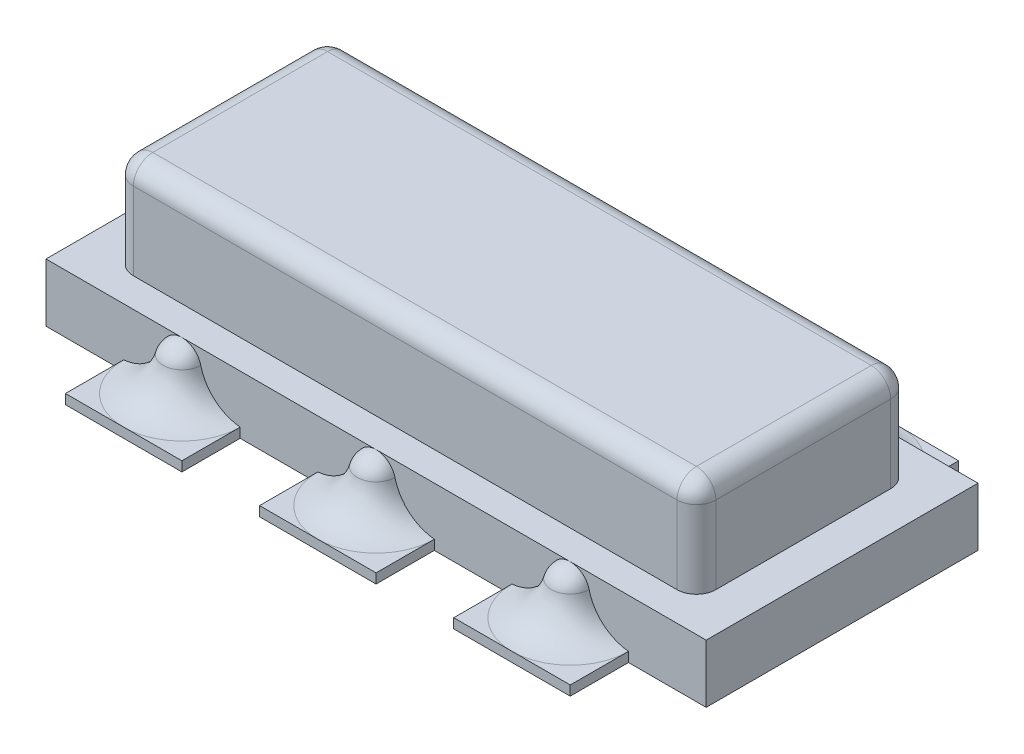
SolidWorks part; units mm, degrees
ref_plane "Front Plane" through (0, 0, 0) normal (0, 0, 1) x (1, 0, 0)
ref_plane "Top Plane" through (0, 0, 0) normal (0, 1, 0) x (1, 0, 0)
ref_plane "Right Plane" through (0, 0, 0) normal (1, 0, 0) x (0, 0, -1)
sketch "Sketch1" plane through (0, 0, 0) normal (0, 1, 0) x (1, 0, 0)
  line L1 (-1.7, 0.7) -> (1.7, 0.7)
  line L2 (-1.7, 0.7) -> (-1.7, -0.7)
  line L3 (-1.7, -0.7) -> (1.7, -0.7)
  line L4 (1.7, 0.7) -> (1.7, -0.7)
  line L5 (-1.7, 0.7) -> (1.7, -0.7) construction
  line L6 (-1.7, -0.7) -> (1.7, 0.7) construction
  point P0 (0, 0)
  dimension "D1" = 1.4
  dimension "D2" = 3.4
extrude "Boss-Extrude1" add sketch "Sketch1" along normal blind 0.3
sketch "Sketch2" plane through (0, 0.3, 0) normal (0, 1, 0) x (1, 0, 0)
  line L1 (-1.5, 0.55) -> (1.5, 0.55)
  line L2 (-1.5, 0.55) -> (-1.5, -0.55)
  line L3 (-1.5, -0.55) -> (1.5, -0.55)
  line L4 (1.5, 0.55) -> (1.5, -0.55)
  line L5 (-1.5, 0.55) -> (1.5, -0.55) construction
  line L6 (-1.5, -0.55) -> (1.5, 0.55) construction
  point P0 (0, 0)
  dimension "D1" = 1.1
  dimension "D2" = 3
extrude "Boss-Extrude2" add sketch "Sketch2" along normal blind 0.5 separate body
fillet "Fillet1" radius 0.1 8 edges at (-1.5, 0.55, 0.55) (-1.5, 0.55, -0.55) (1.5, 0.55, -0.55) (1.5, 0.55, 0.55) (0, 0.8, 0.55) (-1.5, 0.8, 0) (0, 0.8, -0.55) (1.5, 0.8, 0)
sketch "Sketch3" plane through (0, 0, 0) normal (0, 1, 0) x (1, 0, 0)
  line L0 (1, -1) -> (1, 1) construction
  line L1 (-0.3, 1) -> (0.3, 1)
  line L2 (-0.3, 1) -> (-0.3, -1)
  line L3 (-0.3, -1) -> (0.3, -1)
  line L4 (0.3, 1) -> (0.3, -1)
  line L5 (-0.3, 1) -> (0.3, -1) construction
  line L6 (-0.3, -1) -> (0.3, 1) construction
  line L7 (0.7, 1) -> (1.3, 1)
  line L8 (0.7, 1) -> (0.7, -1)
  line L9 (0.7, -1) -> (1.3, -1)
  line L10 (1.3, 1) -> (1.3, -1)
  line L11 (0.7, 1) -> (1.3, -1) construction
  line L12 (0.7, -1) -> (1.3, 1) construction
  line L13 (-1.3, 1) -> (-0.7, 1)
  line L14 (-1.3, 1) -> (-1.3, -1)
  line L15 (-1.3, -1) -> (-0.7, -1)
  line L16 (-0.7, 1) -> (-0.7, -1)
  line L17 (-1.3, 1) -> (-0.7, -1) construction
  line L18 (-1.3, -1) -> (-0.7, 1) construction
  point P0 (0, 0)
  point P5 (1, 0)
  point P11 (-1, 0)
  dimension "D1" = 2
  dimension "D2" = 0.6
  dimension "D3" = 1
  dimension "D4" = 1
extrude "Boss-Extrude3" add sketch "Sketch3" along normal blind 0.05
ref_plane "Plane1" through (1, 0, 0) normal (-1, 0, 0) x (0, 0, 1)
sketch "Sketch5" plane through (1, 0, 0) normal (-1, 0, 0) x (0, 0, 1)
  line L0 (0.7, 0.3) -> (0.7, 0) construction
  line L1 (0.7, 0.3) -> (0.7, 0.05)
  line L2 (0.7, 0.05) -> (1, 0.05) construction
  line L3 (0.7, 0.05) -> (1, 0.05)
  line L4 (0.7, 0.5213) -> (0.7, -0.4213) construction
  line L5 (0.7, 0.3) -> (0.5608, 0.3) construction
  arc A0 (0.7, 0.3) -> (0.7971, 0.224) centre (0.7, 0.2) cw
  arc A1 (0.7971, 0.224) -> (1, 0.05) centre (1.0204, 0.2791) ccw
  point P10 (0.7, 0.05)
  dimension "D1" = 0.1
  dimension "D2" = 0.23
  dimension "D3" = 0.4713
revolve "Revolve1" add sketch "Sketch5" angle 360 mid plane about L4
pattern_linear "LPattern2" count 3 spacing 1 along (-1, 0, 0) count 2 spacing 1.4 along (0, 0, -1) of "Revolve1"
